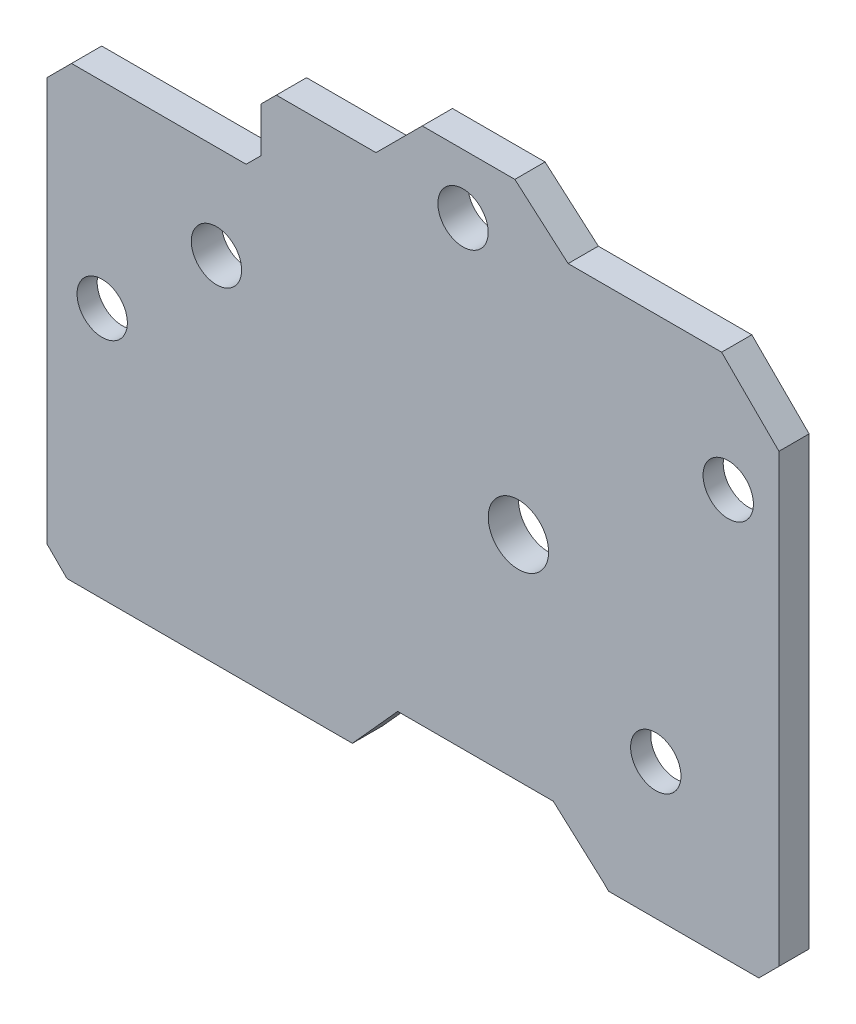
SolidWorks part; units mm, degrees
ref_plane "정면" through (0, 0, 0) normal (0, 0, 1) x (1, 0, 0)
ref_plane "윗면" through (0, 0, 0) normal (0, 1, 0) x (1, 0, 0)
ref_plane "우측면" through (0, 0, 0) normal (1, 0, 0) x (0, 0, -1)
sketch "스케치1" plane through (0, 0, 0) normal (0, 0, 1) x (1, 0, 0)
  line L0 (-7.6943, -28.1969) -> (-3.1923, -23.1969)
  line L1 (-0.7492, 28.4031) -> (8.4508, 28.4031)
  line L2 (-43.0492, 8.9031) -> (-43.0492, -28.1969)
  line L3 (-43.0492, -28.1969) -> (-7.6943, -28.1969)
  line L4 (40.6508, 12.1831) -> (40.6508, -28.1969)
  line L5 (-3.1923, -23.1969) -> (12.2677, -23.1969)
  line L6 (12.2677, -23.1969) -> (17.8208, -28.1969)
  line L7 (17.8208, -28.1969) -> (40.6508, -28.1969)
  line L8 (-28.1492, 23.8031) -> (-43.0492, 8.9031)
  line L9 (28.9925, 23.8031) -> (40.6508, 12.1831)
  line L10 (-0.7492, 28.4031) -> (-5.3492, 23.8031)
  line L11 (-5.3492, 23.8031) -> (-28.1492, 23.8031)
  line L12 (8.4508, 28.4031) -> (13.7425, 23.8031)
  line L13 (13.7425, 23.8031) -> (28.9925, 23.8031)
  line L14 (13.7425, 23.8031) -> (9.84, 23.8031) construction
  line L15 (27.6508, -14.6969) -> (27.6508, -28.1969)
  line L16 (27.6508, -28.1969) -> (17.8208, -28.1969)
  line L17 (17.2508, -27.6836) -> (17.2508, -14.6969)
  line L18 (-29.9492, -7.7002) -> (-29.9492, -28.1969)
  line L19 (-27.3492, -28.1969) -> (-37.7492, -28.1969)
  line L20 (-37.7492, -28.1969) -> (-37.7492, -3.1969)
  circle A0 centre (-21.1975, 7.0131) radius 2.5
  circle A1 centre (3.3025, 22.5131) radius 2.5
  circle A2 centre (8.8025, -1.9869) radius 3
  arc A3 (-29.9492, -7.7002) -> (-37.7492, -3.1969) centre (-32.5492, -3.1969) ccw
  circle A4 centre (-32.5492, -3.1969) radius 2.5
  circle A5 centre (22.4508, -14.6969) radius 5.2
  circle A6 centre (22.4508, -14.6969) radius 2.5
  point P0 (-1.1998, -0.6969)
  dimension "D1" = 5
  dimension "D2" = 5
  dimension "D3" = 6
  dimension "D9" = 5
  dimension "D10" = 10.4
  dimension "D11" = 5
  dimension "D12" = 10.4
  dimension "D13" = 10.5
  dimension "D4" = 24.5
  dimension "D5" = 24.5
  dimension "D6" = 30
  dimension "D7" = 15.5
  dimension "D8" = 9
  dimension "D14" = 25
  dimension "D15" = 18.2
  dimension "D16" = 13.5
  dimension "D17" = 5
  dimension "D18" = 52
  dimension "D19" = 4.6
  dimension "D20" = 9.2
  dimension "D21" = 41
  dimension "D22" = 15.25
  dimension "D23" = 83.7
  dimension "D24" = 37.1
  dimension "D25" = 135
  dimension "D26" = 40.38
  dimension "D27" = 22.8
  dimension "D28" = 135
  dimension "D29" = 15.46
  dimension "D30" = 132
  dimension "D31" = 22.83
  dimension "D32" = 10.44
  dimension "D33" = 5.89
extrude "보스-돌출1" add sketch "스케치1" along normal blind 3 contours L13 L12 L1 L10 L11 L8 L2 L3 L0 L5 L6 L7 L4 L9 A5 A3 A2 A1 A0
sketch "스케치3" plane through (0, 0, 3) normal (0, 0, 1) x (1, 0, 0)
  line L0 (27.6508, -14.6969) -> (27.6508, -28.1969)
  line L1 (17.2508, -14.6969) -> (17.2508, -27.6836)
  line L2 (17.2508, -27.6836) -> (17.764, -28.1969)
  line L3 (17.764, -28.1969) -> (27.6508, -28.1969)
  line L4 (-29.9492, -7.7002) -> (-29.9492, -28.1969)
  line L5 (-30.0492, -28.1969) -> (-37.7492, -28.1969)
  line L6 (-37.7492, -28.1969) -> (-37.7492, -3.1969)
  line L8 (-29.9492, -28.1969) -> (-30.0492, -28.1969)
  circle A0 centre (-32.5492, -3.1969) radius 5.2 construction
  arc A1 (-27.3492, -3.1969) -> (-37.7492, -3.1969) centre (-32.5492, -3.1969) ccw
  circle A2 centre (-32.5492, -3.1969) radius 2.5
  circle A3 centre (22.4508, -14.6969) radius 5.2 construction
  arc A4 (27.6508, -14.6969) -> (17.2508, -14.6969) centre (22.4508, -14.6969) ccw
  circle A5 centre (22.4508, -14.6969) radius 2.5
  arc A6 (-29.9492, -7.7002) -> (-37.7492, -3.1969) centre (-32.5492, -3.1969) ccw
  dimension "D1" = 5
  dimension "D2" = 5
  dimension "D3" = 135
extrude "보스-돌출3" add sketch "스케치3" against normal blind 2
sketch "스케치6" plane through (0, 0, 3) normal (0, 0, 1) x (1, 0, 0)
  line L0 (26.4064, 8.0587) -> (32.8952, 8.0587) construction
  line L1 (33.8952, 9.0587) -> (33.8952, 15.5475) construction
  line L2 (32.8952, 16.5475) -> (29.6508, 16.5475) construction
  line L3 (25.4064, 9.0587) -> (25.4064, 12.3031) construction
  line L4 (40.6508, 12.1831) -> (40.6508, -28.1969) construction
  line L5 (17.764, -28.1969) -> (40.6508, -28.1969) construction
  arc A0 (29.6508, 16.5475) -> (25.4064, 12.3031) centre (29.6508, 12.3031) ccw construction
  arc A1 (26.4064, 8.0587) -> (25.4064, 9.0587) centre (26.4064, 9.0587) cw construction
  arc A2 (32.8952, 8.0587) -> (33.8952, 9.0587) centre (32.8952, 9.0587) ccw construction
  arc A3 (33.8952, 15.5475) -> (32.8952, 16.5475) centre (32.8952, 15.5475) ccw construction
  dimension "D1" = 1
  dimension "D2" = 11
  dimension "D3" = 40.5
  dimension "D4" = 8.4888
sketch "스케치7" plane through (0, 0, 0) normal (0, 0, -1) x (-1, 0, 0)
  line L0 (-33.8952, 9.0587) -> (-33.8952, 15.5475) construction
  line L1 (-32.8952, 16.5475) -> (-29.6508, 16.5475) construction
  line L2 (-25.4064, 9.0587) -> (-25.4064, 12.3031) construction
  line L3 (-26.4064, 8.0587) -> (-32.8952, 8.0587) construction
  line L4 (-33.8952, 9.0587) -> (-33.8952, 15.5475)
  line L5 (-32.8952, 16.5475) -> (-29.6508, 16.5475)
  line L6 (-25.4064, 9.0587) -> (-25.4064, 12.3031)
  line L7 (-26.4064, 8.0587) -> (-32.8952, 8.0587)
  line L8 (-26.4064, 7.9087) -> (-32.8952, 7.9087)
  line L9 (-34.0452, 9.0587) -> (-34.0452, 15.5475)
  line L10 (-32.8952, 16.6975) -> (-29.6508, 16.6975)
  line L11 (-25.2564, 9.0587) -> (-25.2564, 12.3031)
  line L14 (-13.7425, 23.8031) -> (-28.9925, 23.8031)
  line L15 (-28.9925, 23.8031) -> (-40.6508, 12.1831)
  line L16 (-40.6508, 12.1831) -> (-40.6508, -28.1969)
  line L17 (-40.6508, -28.1969) -> (-27.6508, -28.1969)
  line L18 (-17.2508, -27.6836) -> (-12.2677, -23.1969)
  line L19 (-12.2677, -23.1969) -> (3.1923, -23.1969)
  line L20 (3.1923, -23.1969) -> (7.6943, -28.1969)
  line L21 (7.6943, -28.1969) -> (29.9492, -28.1969)
  line L22 (43.0492, -28.1969) -> (43.0492, 8.9031)
  line L23 (43.0492, 8.9031) -> (28.1492, 23.8031)
  line L24 (28.1492, 23.8031) -> (5.3492, 23.8031)
  line L25 (5.3492, 23.8031) -> (0.7492, 28.4031)
  line L26 (0.7492, 28.4031) -> (-8.4508, 28.4031)
  line L27 (-8.4508, 28.4031) -> (-13.7425, 23.8031)
  line L28 (-13.7425, 23.8031) -> (-28.9925, 23.8031)
  line L29 (-28.9925, 23.8031) -> (-40.6508, 12.1831)
  line L30 (-40.6508, 12.1831) -> (-40.6508, -28.1969)
  line L31 (-40.6508, -28.1969) -> (-27.6508, -28.1969)
  line L32 (-17.2508, -27.6836) -> (-12.2677, -23.1969)
  line L33 (-12.2677, -23.1969) -> (3.1923, -23.1969)
  line L34 (3.1923, -23.1969) -> (7.6943, -28.1969)
  line L35 (7.6943, -28.1969) -> (29.9492, -28.1969)
  line L36 (43.0492, -28.1969) -> (43.0492, 8.9031)
  line L37 (43.0492, 8.9031) -> (28.1492, 23.8031)
  line L38 (28.1492, 23.8031) -> (5.3492, 23.8031)
  line L39 (5.3492, 23.8031) -> (0.7492, 28.4031)
  line L40 (0.7492, 28.4031) -> (-8.4508, 28.4031)
  line L41 (-8.4508, 28.4031) -> (-13.7425, 23.8031)
  line L59 (29.9492, -28.1969) -> (29.9492, -7.7002)
  line L60 (29.9492, -28.1969) -> (29.9492, -7.7002)
  line L61 (-27.6508, -28.1969) -> (-27.6508, -14.6969)
  line L62 (-27.6508, -28.1969) -> (-27.6508, -14.6969)
  line L63 (-17.2508, -14.6969) -> (-17.2508, -27.6836)
  line L64 (-17.2508, -14.6969) -> (-17.2508, -27.6836)
  line L65 (37.7492, -3.1969) -> (37.7492, -28.1969)
  line L66 (37.7492, -3.1969) -> (37.7492, -28.1969)
  line L67 (37.7492, -28.1969) -> (43.0492, -28.1969)
  line L68 (37.7492, -28.1969) -> (43.0492, -28.1969)
  arc A0 (-32.8952, 16.5475) -> (-33.8952, 15.5475) centre (-32.8952, 15.5475) ccw construction
  arc A1 (-25.4064, 12.3031) -> (-29.6508, 16.5475) centre (-29.6508, 12.3031) ccw construction
  arc A2 (-26.4064, 8.0587) -> (-25.4064, 9.0587) centre (-26.4064, 9.0587) ccw construction
  arc A3 (-33.8952, 9.0587) -> (-32.8952, 8.0587) centre (-32.8952, 9.0587) ccw construction
  arc A4 (-32.8952, 16.5475) -> (-33.8952, 15.5475) centre (-32.8952, 15.5475) ccw
  arc A5 (-25.4064, 12.3031) -> (-29.6508, 16.5475) centre (-29.6508, 12.3031) ccw
  arc A6 (-26.4064, 8.0587) -> (-25.4064, 9.0587) centre (-26.4064, 9.0587) ccw
  arc A7 (-33.8952, 9.0587) -> (-32.8952, 8.0587) centre (-32.8952, 9.0587) ccw
  circle A8 centre (8.0492, -24.1969) radius 2.5
  circle A9 centre (6.1492, 20.8031) radius 2.5
  arc A10 (-34.0452, 9.0587) -> (-32.8952, 7.9087) centre (-32.8952, 9.0587) ccw
  arc A11 (-32.8952, 16.6975) -> (-34.0452, 15.5475) centre (-32.8952, 15.5475) ccw
  arc A12 (-25.2564, 12.3031) -> (-29.6508, 16.6975) centre (-29.6508, 12.3031) ccw
  arc A13 (-26.4064, 7.9087) -> (-25.2564, 9.0587) centre (-26.4064, 9.0587) ccw
  circle A14 centre (6.1492, 20.8031) radius 2.65
  circle A15 centre (8.0492, -24.1969) radius 2.65
  arc A18 (37.7492, -3.1969) -> (29.9492, -7.7002) centre (32.5492, -3.1969) ccw
  arc A19 (37.7492, -3.1969) -> (29.9492, -7.7002) centre (32.5492, -3.1969) ccw
  arc A20 (-17.2508, -14.6969) -> (-27.6508, -14.6969) centre (-22.4508, -14.6969) ccw
  arc A21 (-17.2508, -14.6969) -> (-27.6508, -14.6969) centre (-22.4508, -14.6969) ccw
  dimension "D2" = 5
  dimension "D5" = 5
  dimension "D3" = 4
  dimension "D4" = 35
  dimension "D6" = 3
  dimension "D7" = 22
  dimension "D1" = 0
  dimension "D8" = 0.15
extrude "컷-돌출1" cut sketch "스케치7" against normal blind 1 contours A8 | A9 | L8 A13 L11 A12 L10 A11 L9 A10 A7 L4 A4 L5 A5 L6 A6 L7 | A15 A8 | L38 A14 A9
chamfer "모따기1" distance 1 angle 45 2 edges at (-43.0492, -28.1969, 1.5) (40.6508, -28.1969, 1.5)
sketch "스케치10" plane through (0, 0, 1) normal (0, 0, -1) x (-1, 0, 0)
  line L0 (-33.7084, 16.3607) -> (-25.5932, 8.2456) construction
  arc A0 (-32.8952, 16.6975) -> (-34.0452, 15.5475) centre (-32.8952, 15.5475) ccw construction
  arc A1 (-26.4064, 7.9087) -> (-25.2564, 9.0587) centre (-26.4064, 9.0587) ccw construction
  circle A2 centre (-29.6508, 12.3031) radius 2.5
  dimension "D1" = 5
extrude "컷-돌출3" cut sketch "스케치10" against normal up to next
sketch "스케치11" plane through (0, 0, 3) normal (0, 0, 1) x (1, 0, 0)
  point P1 (29.6508, 12.3031)
  point P2 (22.4508, -14.6969)
  point P3 (-32.5492, -3.1969)
sketch "스케치12" plane through (0, 0, 0) normal (0, 0, -1) x (-1, 0, 0)
  line L0 (16.7492, 23.8031) -> (16.7492, 16.3531)
  line L1 (5.3492, 23.8031) -> (28.1492, 23.8031) construction
  line L2 (16.7492, 16.3531) -> (35.5992, 16.3531)
  line L3 (28.1492, 23.8031) -> (43.0492, 8.9031) construction
  line L4 (35.5992, 16.3531) -> (28.1492, 23.8031)
  line L5 (28.1492, 23.8031) -> (16.7492, 23.8031)
extrude "컷-돌출4" cut sketch "스케치12" against normal up to next
chamfer "모따기2" distance 1.5 angle 45 2 edges at (-16.7492, 23.8031, 1.5) (-16.7492, 16.3531, 1.5)
sketch "스케치13" plane through (0, 0, 0) normal (0, 0, -1) x (-1, 0, 0)
  line L2 (-34.6893, 18.1251) -> (-34.6893, -28.1969)
  line L3 (38.0492, 13.9031) -> (43.0492, 8.9031)
  line L4 (43.0492, 8.9031) -> (43.0492, -27.1969)
  line L5 (43.0492, -27.1969) -> (42.0492, -28.1969)
  line L6 (42.0492, -28.1969) -> (38.0492, -28.1969)
  line L7 (-40.6508, 12.1831) -> (-34.6893, 18.1251)
  line L8 (-28.9925, 23.8031) -> (-40.6508, 12.1831) construction
  line L17 (-40.6508, 12.1831) -> (-40.6508, -27.1969)
  line L18 (-40.6508, -27.1969) -> (-39.6508, -28.1969)
  line L19 (-39.6508, -28.1969) -> (-34.6893, -28.1969)
  line L20 (38.0492, 13.9031) -> (38.0492, -28.1969)
  dimension "D1" = 5.5
  dimension "D2" = 5.0385
extrude "컷-돌출5" cut sketch "스케치13" against normal up to next
chamfer "모따기3" distance 2 angle 45 2 edges at (-38.0492, -28.1969, 1.5) (34.6893, -28.1969, 1.5)
sketch "스케치14" plane through (0, 0, 0) normal (0, 0, -1) x (-1, 0, 0)
  line L0 (-34.6893, -4.0359) -> (37.7492, -4.0359) construction
  line L1 (-34.6893, -26.1969) -> (-34.6893, 18.1251) construction
  line L2 (37.7492, -26.4969) -> (37.7492, -3.1969) construction
